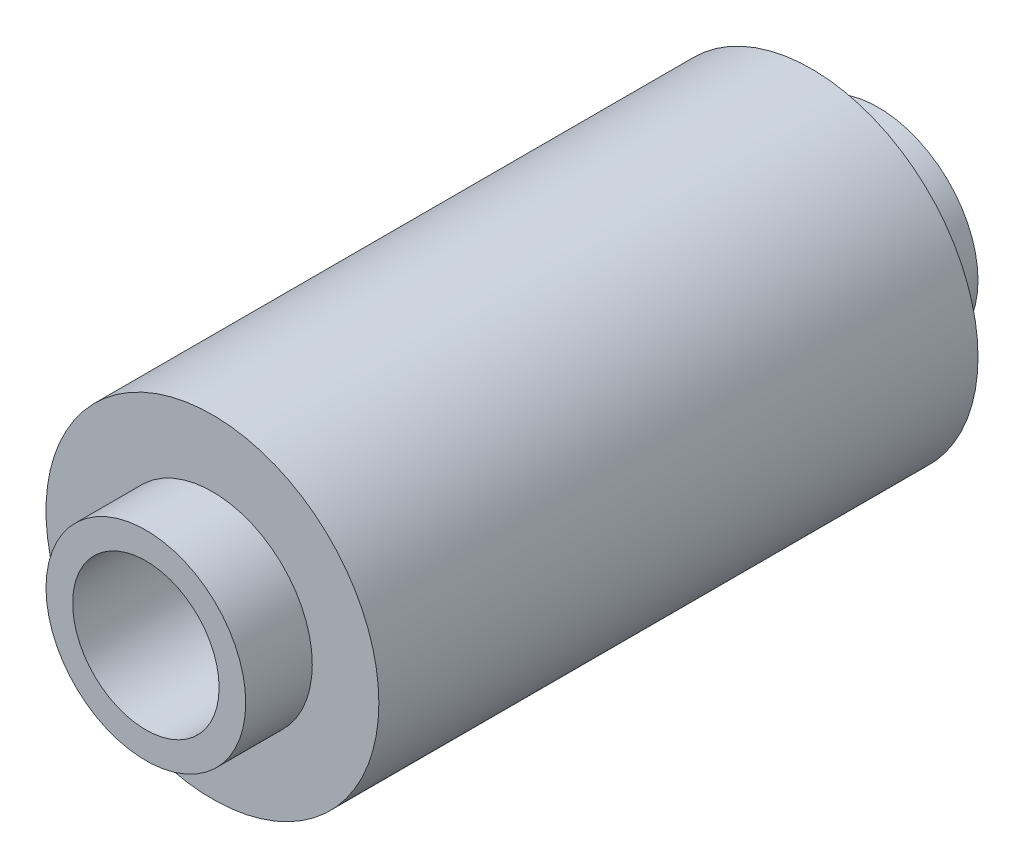
SolidWorks part; units mm, degrees
material "AISI 4340 Steel, normalized"
ref_plane "Front Plane" through (0, 0, 0) normal (0, 0, 1) x (1, 0, 0)
ref_plane "Top Plane" through (0, 0, 0) normal (0, 1, 0) x (1, 0, 0)
ref_plane "Right Plane" through (0, 0, 0) normal (1, 0, 0) x (0, 0, -1)
sketch "Sketch1" plane through (0, 0, 0) normal (0, 0, 1) x (1, 0, 0)
  circle A0 centre (0, 0) radius 2.5
  circle A1 centre (0, 0) radius 1.1
extrude "Shoulder_Spacer_L9" add sketch "Sketch1" along normal blind 9
sketch "Sketch2" plane through (0, 0, 0) normal (0, 0, 1) x (1, 0, 0)
  circle A0 centre (0, 0) radius 1.5
  circle A1 centre (0, 0) radius 1.1
extrude "Lower_Torque_Pilot_D3" add sketch "Sketch2" along normal blind 1 from offset 1
sketch "Sketch3" plane through (0, 0, 0) normal (0, 0, 1) x (1, 0, 0)
  circle A0 centre (0, 0) radius 1.5
  circle A1 centre (0, 0) radius 1.1
extrude "Upper_Torque_Pilot_D3" add sketch "Sketch3" along normal blind 1 from offset 9
